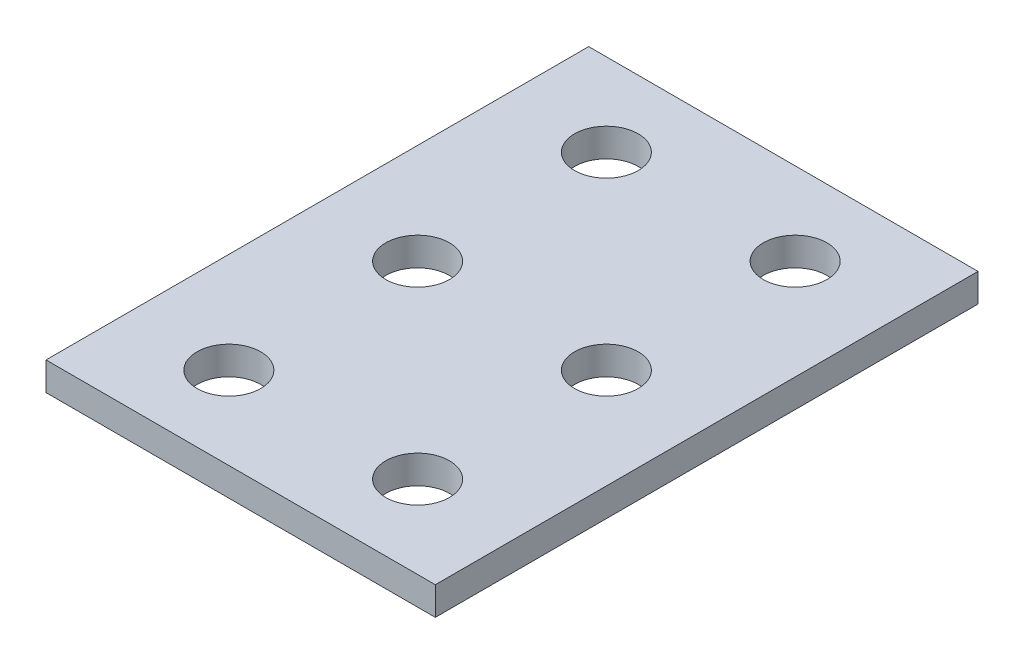
SolidWorks part; units mm, degrees
ref_plane "前视基准面" through (0, 0, 0) normal (0, 0, 1) x (1, 0, 0)
ref_plane "上视基准面" through (0, 0, 0) normal (0, 1, 0) x (1, 0, 0)
ref_plane "右视基准面" through (0, 0, 0) normal (1, 0, 0) x (0, 0, -1)
sketch "草图3" plane through (0, 0, 0) normal (0, 1, 0) x (1, 0, 0)
  line L1 (0, 0) -> (165, 0)
  line L2 (0, 0) -> (0, 230)
  line L3 (0, 230) -> (165, 230)
  line L4 (165, 0) -> (165, 230)
  dimension "D1" = 165
  dimension "D2" = 230
extrude "凸台-拉伸2" add sketch "草图3" along normal blind 12
sketch "草图4" plane through (0, 12, 0) normal (0, 1, 0) x (1, 0, 0)
  line L0 (82.5, -770) -> (82.5, 49230) construction
  line L1 (165, 230) -> (0, 230) construction
  line L2 (42.5, -912.262) -> (42.5, 49087.738) construction
  line L3 (122.5, -919.4065) -> (122.5, 49080.5935) construction
  line L4 (-917.5, 195) -> (49082.5, 195) construction
  line L5 (-835, 115) -> (49165, 115) construction
  line L6 (165, 0) -> (165, 230) construction
  line L7 (-853.5754, 35) -> (49146.4246, 35) construction
  circle A0 centre (42.5, 195) radius 13.5
  circle A2 centre (122.5, 195) radius 13.5
  circle A3 centre (42.5, 115) radius 13.5
  circle A5 centre (122.5, 115) radius 13.5
  circle A6 centre (42.5, 35) radius 13.5
  circle A8 centre (122.5, 35) radius 13.5
  point P5 (82.5, 230)
  point P16 (165, 115)
  dimension "D5" = 27
  dimension "D1" = 40
  dimension "D2" = 40
  dimension "D3" = 80
  dimension "D4" = 80
extrude "切除-拉伸2" cut sketch "草图4" against normal through all
